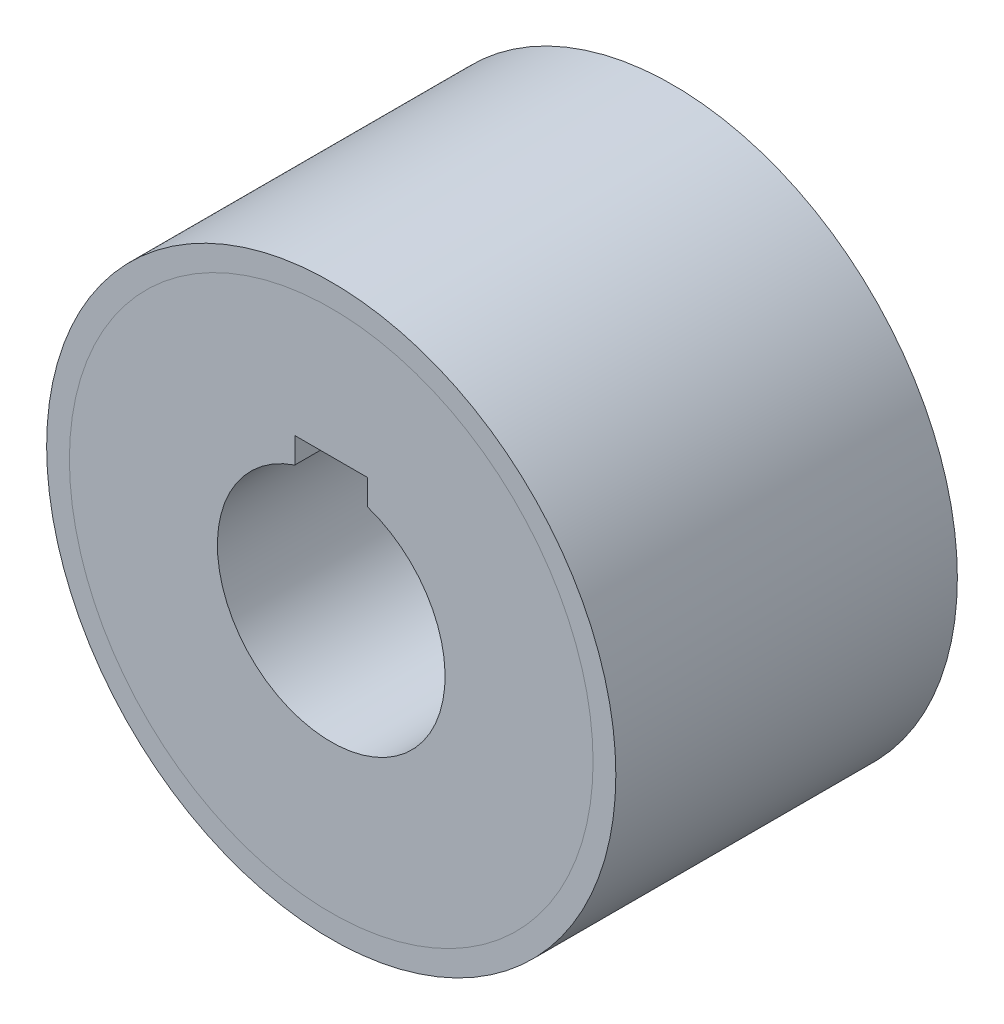
SolidWorks part; units mm, degrees
material "1.7225 (42CrMo4)"
ref_plane "Front Plane" through (0, 0, 0) normal (0, 0, 1) x (1, 0, 0)
ref_plane "Top Plane" through (0, 0, 0) normal (0, 1, 0) x (1, 0, 0)
ref_plane "Right Plane" through (0, 0, 0) normal (1, 0, 0) x (0, 0, -1)
sketch "Sketch1" plane through (0, 0, 0) normal (0, 0, 1) x (1, 0, 0)
  circle A0 centre (0, 0) radius 57.5
  dimension "D1" = 115
extrude "Boss-Extrude1" add sketch "Sketch1" along normal blind 75
sketch "Sketch2" plane through (0, 0, 75) normal (0, 0, 1) x (1, 0, 0)
  circle A0 centre (0, 0) radius 25
  dimension "D1" = 50
extrude "Cut-Extrude1" cut sketch "Sketch2" against normal through all
sketch "Sketch3" plane through (0, 0, 75) normal (0, 0, 1) x (1, 0, 0)
  line L0 (0, 0) -> (0, 57.5) construction
  line L1 (-8, 23.6854) -> (-8, 29.3)
  line L2 (-8, 29.3) -> (8, 29.3)
  line L3 (8, 23.6854) -> (8, 29.3)
  circle A0 centre (0, 0) radius 57.5 construction
  circle A1 centre (0, 0) radius 25 construction
  arc A2 (8, 23.6854) -> (-8, 23.6854) centre (0, 0) ccw
  point P11 (0, 29.3)
  dimension "D1" = 16
  dimension "D2" = 4.3
extrude "Cut-Extrude2" cut sketch "Sketch3" against normal through all
sketch "Sketch4" plane through (0, 0, 75) normal (0, 0, 1) x (1, 0, 0)
  circle A1 centre (0, 0) radius 62.5
  circle A2 centre (0, 0) radius 57.5 construction
  circle A3 centre (0, 0) radius 57.5
  dimension "D1" = 125
extrude "Boss-Extrude3" add sketch "Sketch4" against normal up to surface (75 mm away) separate body up to face at (0, 14.3214, 0)
